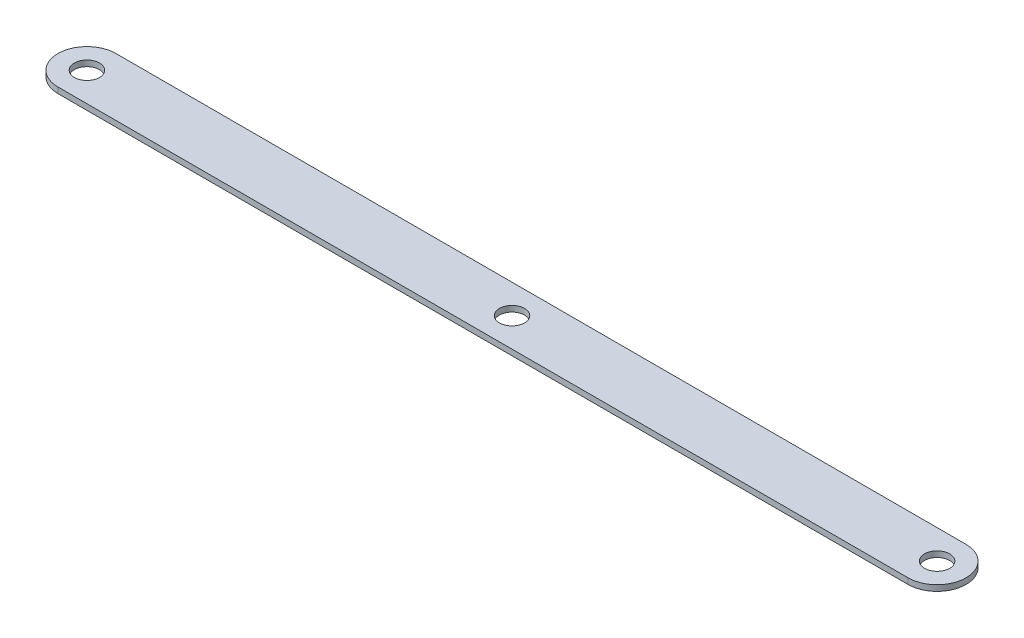
SolidWorks part; units mm, degrees
ref_plane "前视基准面" through (0, 0, 0) normal (0, 0, 1) x (1, 0, 0)
ref_plane "上视基准面" through (0, 0, 0) normal (0, 1, 0) x (1, 0, 0)
ref_plane "右视基准面" through (0, 0, 0) normal (1, 0, 0) x (0, 0, -1)
sketch "草图1" plane through (0, 0, 0) normal (0, 1, 0) x (1, 0, 0)
  line L0 (110, 0) -> (-110, 0) construction
  line L2 (110, -7.5) -> (-110, -7.5)
  line L3 (110, 7.5) -> (-110, 7.5)
  arc A0 (110, -7.5) -> (110, 7.5) centre (110, 0) ccw
  arc A1 (-110, 7.5) -> (-110, -7.5) centre (-110, 0) ccw
  point P5 (0, 0)
  dimension "D2" = 7.5
  dimension "D1" = 110
extrude "凸台-拉伸1" add sketch "草图1" along normal blind 1.5
sketch "草图2" plane through (0, 1.5, 0) normal (0, 1, 0) x (1, 0, 0)
  circle A0 centre (110, 0) radius 3.25
  circle A1 centre (0, 0) radius 3.25
  circle A2 centre (-110, 0) radius 3.25
  arc A3 (-110, 7.5) -> (-110, -7.5) centre (-110, 0) ccw construction
  arc A4 (110, -7.5) -> (110, 7.5) centre (110, 0) ccw construction
  dimension "D1" = 6.5
extrude "切除-拉伸1" cut sketch "草图2" against normal blind 1.5
